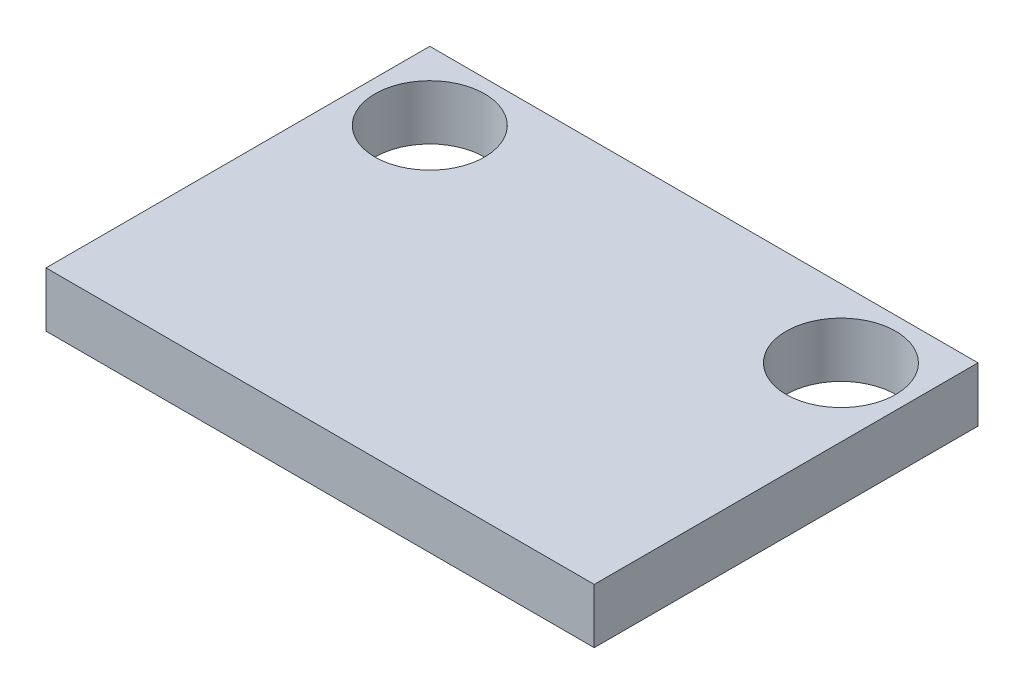
SolidWorks part; units mm, degrees
material "Acrylic (Medium-high impact)"
ref_plane "Front Plane" through (0, 0, 0) normal (0, 0, 1) x (1, 0, 0)
ref_plane "Top Plane" through (0, 0, 0) normal (0, 1, 0) x (1, 0, 0)
ref_plane "Right Plane" through (0, 0, 0) normal (1, 0, 0) x (0, 0, -1)
sketch "Sketch1" plane through (0, 0, 0) normal (0, 1, 0) x (1, 0, 0)
  line L1 (-10, 7) -> (10, 7)
  line L2 (-10, 7) -> (-10, -7)
  line L3 (-10, -7) -> (10, -7)
  line L4 (10, 7) -> (10, -7)
  line L5 (-10, 7) -> (10, -7) construction
  line L6 (-10, -7) -> (10, 7) construction
  circle A0 centre (-7.5, 4.5) radius 2
  circle A1 centre (7.5, 4.5) radius 2
  point P0 (0, 0)
  dimension "D3" = 15
  dimension "D5" = 4
  dimension "D6" = 4
  dimension "D7" = 2.5
  dimension "D1" = 14
  dimension "D2" = 20
  dimension "D4" = 7.5
extrude "Boss-Extrude1" add sketch "Sketch1" along normal blind 2
